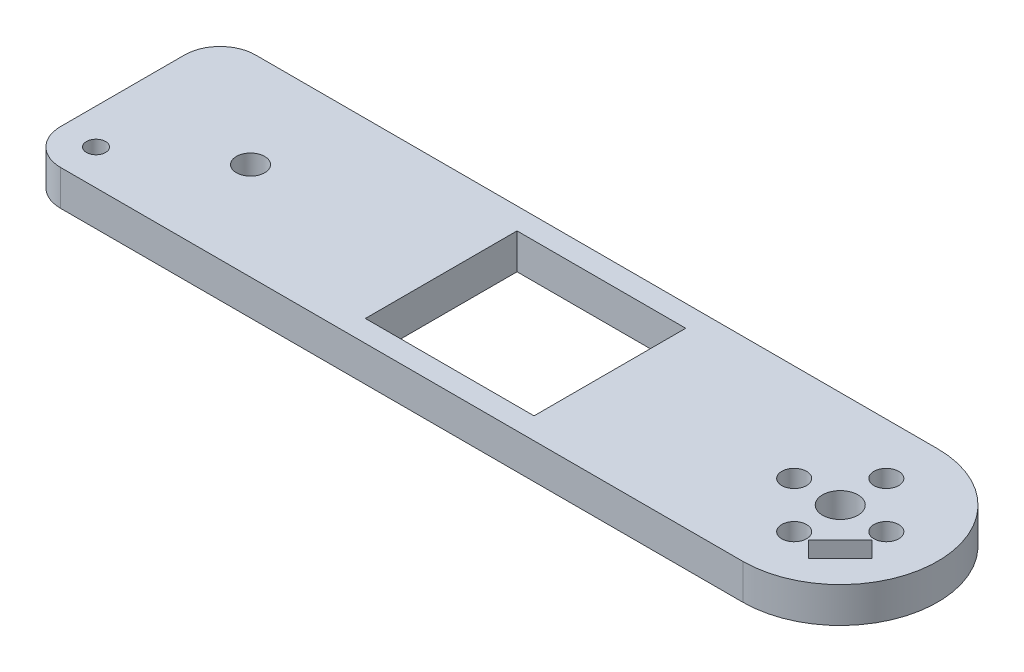
SolidWorks part; units mm, degrees
material "ABS"
ref_plane "Front Plane" through (0, 0, 0) normal (0, 0, 1) x (1, 0, 0)
ref_plane "Top Plane" through (0, 0, 0) normal (0, 1, 0) x (1, 0, 0)
ref_plane "Right Plane" through (0, 0, 0) normal (1, 0, 0) x (0, 0, -1)
sketch "Sketch1" plane through (0, 0, 0) normal (0, 1, 0) x (1, 0, 0)
  line L1 (87.5, -27.5) -> (-87.5, -27.5)
  line L2 (87.5, -27.5) -> (87.5, 27.5)
  line L3 (87.5, 27.5) -> (-87.5, 27.5)
  line L4 (-87.5, -27.5) -> (-87.5, 27.5)
  line L5 (87.5, -27.5) -> (-87.5, 27.5) construction
  line L6 (87.5, 27.5) -> (-87.5, -27.5) construction
  point P0 (0, 0)
  dimension "D1" = 175
  dimension "D2" = 55
extrude "Boss-Extrude1" add sketch "Sketch1" along normal blind 10
sketch "Sketch2" plane through (0, 0, 0) normal (0, -1, 0) x (1, 0, 0)
  line L0 (-87.5, 27.5) -> (-87.5, -27.5)
  line L1 (87.5, 27.5) -> (87.5, -27.5)
  line L2 (87.5, -27.5) -> (-87.5, -27.5) construction
  line L3 (0, 27.5) -> (0, 0) construction
  line L4 (-87.5, 27.5) -> (87.5, 27.5) construction
  line L5 (-87.5, 27.5) -> (-115, 27.5)
  line L6 (-115, 27.5) -> (-115, -27.5)
  line L7 (-115, -27.5) -> (-87.5, -27.5)
  line L8 (87.5, 27.5) -> (87.5, -27.5) construction
  line L9 (-87.5, -27.5) -> (-87.5, 27.5) construction
  arc A0 (-87.5, -27.5) -> (-87.5, 27.5) centre (-87.5, 0) cw construction
  arc A1 (87.5, -27.5) -> (87.5, 27.5) centre (87.5, 0) ccw
extrude "Boss-Extrude2" add sketch "Sketch2" against normal up to surface (10 mm away) up to face at (0, 10, 0)
sketch "Sketch4" plane through (0, 10, 0) normal (0, 1, 0) x (1, 0, 0)
  circle A0 centre (87.5, 0) radius 12.065
  dimension "D1" = 24.13
hole_wizard "M8 Clearance Hole1" positions "Sketch5" profile "Sketch6" hole size "M8" standard "ANSI Metric" end condition through all
sketch "Sketch5" plane through (0, 0, 0) normal (0, -1, 0) x (-1, 0, 0)
  point P0 (-87.5, 0)
sketch "Sketch6" plane through (87.5, 0, 0) normal (1, 0, 0) x (0, 0, -1)
  line L0 (0, 0) -> (0, 10)
  line L1 (0, 10) -> (5, 10)
  line L2 (5, 10) -> (5, 0)
  line L5 (5, 0) -> (0, 0)
  line L11 (0, -6.35) -> (0, 107.95) construction
  dimension "Thru Hole Dia." = 10
  dimension "Thru Hole Depth" = 10
hole_wizard "M6 Clearance Hole1" positions "Sketch9" profile "Sketch8" hole size "M6" standard "ANSI Metric" end condition through all
sketch "Sketch9" plane through (0, 10, 0) normal (0, 1, 0) x (1, 0, 0)
  circle A2 centre (87.5, 0) radius 13
  point P8 (87.5, 13)
  point P12 (74.5, 0)
  point P14 (100.5, 0)
  point P16 (87.5, -13)
  dimension "D2" = 26
sketch "Sketch8" plane through (87.5, 10, -13) normal (1, 0, 0) x (0, 0, 1)
  line L0 (0, 0) -> (0, 10)
  line L1 (0, 10) -> (3.5, 10)
  line L2 (3.5, 10) -> (3.5, 0)
  line L5 (3.5, 0) -> (0, 0)
  line L11 (0, -6.35) -> (0, 107.95) construction
  dimension "Thru Hole Dia." = 7
  dimension "Thru Hole Depth" = 10
fillet "Fillet1" radius 10 2 edges at (-115, 5, 27.5) (-115, 5, -27.5)
sketch "Sketch11" plane through (0, 0, 0) normal (0, -1, 0) x (1, 0, 0)
  line L1 (-24.9, -21.2) -> (17.5, -21.2)
  line L2 (-24.9, -21.2) -> (-24.9, 21.2)
  line L3 (-24.9, 21.2) -> (17.5, 21.2)
  line L4 (17.5, -21.2) -> (17.5, 21.2)
  line L5 (-24.9, -21.2) -> (17.5, 21.2) construction
  line L6 (-24.9, 21.2) -> (17.5, -21.2) construction
  point P4 (-3.7, 0)
  dimension "D1" = 42.4
  dimension "D2" = 70
extrude "Cut-Extrude3" cut sketch "Sketch11" against normal through all
sketch "Sketch12" plane through (0, 0, 0) normal (0, -1, 0) x (1, 0, 0)
  line L2 (-115, 17.5) -> (-115, -17.5) construction
  circle A0 centre (-78.9, 0) radius 4
  point P7 (-115, 0)
  dimension "D1" = 8
  dimension "D2" = 54
extrude "Cut-Extrude4" cut sketch "Sketch12" against normal through all
sketch "Sketch13" plane through (0, 0, 0) normal (0, -1, 0) x (1, 0, 0)
  line L0 (-24.9, -21.2) -> (17.5, -21.2) construction
  line L1 (17.5, 21.2) -> (22.5, 21.2)
  line L2 (17.5, 21.2) -> (17.5, -21.2)
  line L3 (17.5, -21.2) -> (22.5, -21.2)
  line L4 (22.5, 21.2) -> (22.5, -21.2)
  line L5 (17.5, 21.2) -> (22.5, -21.2) construction
  line L6 (17.5, -21.2) -> (22.5, 21.2) construction
  line L7 (-24.9, 21.2) -> (-24.9, -21.2) construction
  line L8 (-24.9, 21.2) -> (22.5, 21.2)
  line L9 (-24.9, 21.2) -> (-24.9, 21.4)
  line L10 (-24.9, 21.4) -> (22.5, 21.4)
  line L11 (22.5, 21.2) -> (22.5, 21.4)
  line L12 (-24.9, 21.2) -> (22.5, 21.4) construction
  line L13 (-24.9, 21.4) -> (22.5, 21.2) construction
  line L14 (22.5, -21.2) -> (-24.9, -21.2)
  line L15 (22.5, -21.2) -> (22.5, -21.4)
  line L16 (22.5, -21.4) -> (-24.9, -21.4)
  line L17 (-24.9, -21.2) -> (-24.9, -21.4)
  line L18 (22.5, -21.2) -> (-24.9, -21.4) construction
  line L19 (22.5, -21.4) -> (-24.9, -21.2) construction
  line L20 (-24.9, -21.4) -> (-25.1, -21.4)
  line L21 (-24.9, -21.4) -> (-24.9, 21.4)
  line L22 (-24.9, 21.4) -> (-25.1, 21.4)
  line L23 (-25.1, -21.4) -> (-25.1, 21.4)
  line L24 (-24.9, -21.4) -> (-25.1, 21.4) construction
  line L25 (-24.9, 21.4) -> (-25.1, -21.4) construction
  line L26 (17.5, 21.2) -> (-24.9, 21.2) construction
  point P4 (20, 0)
  point P12 (-1.2, 21.3)
  point P17 (-1.2, -21.3)
  point P21 (-25, 0)
  line M6 (17.5, -21.2) -> (-24.9, -21.2)
  line M7 (-24.9, -21.2) -> (-24.9, 21.2)
  line M8 (-24.9, 21.2) -> (17.5, 21.2)
  line M9 (17.5, 21.2) -> (17.5, -21.2)
  dimension "D1" = 5
  dimension "D2" = 0.2
  dimension "D3" = 0.2
  dimension "D4" = 0.2
  dimension "D5" = 42.4
  dimension "D6" = 23.7
extrude "Cut-Extrude5" cut sketch "Sketch13" against normal through all contours L23 L20 L17 L9 L22 M7 | L1 L11 L10 L9 M8 | L4 L1 L3 M9 | L17 L16 L15 L3 M6
sketch "Sketch14" plane through (0, 0, 0) normal (0, -1, 0) x (1, 0, 0)
  line L0 (91.5411, 13.0214) -> (100.5214, 4.0411)
  line L1 (91.5411, 13.0214) -> (96.0312, 17.5115)
  line L2 (100.5214, 4.0411) -> (105.0115, 8.5312)
  line L3 (96.0312, 17.5115) -> (105.0115, 8.5312)
  line L4 (83.9645, 3.5355) -> (91.0355, -3.5355) construction
  line L5 (87.5, 5) -> (87.5, -5) construction
  line L6 (87.5, 0) -> (96.0312, 8.5312) construction
  circle A1 centre (87.5, 0) radius 5 construction
  circle A2 centre (87.5, 0) radius 12.065 construction
  point P13 (87.5, 0)
  dimension "D4" = 45
  dimension "D1" = 45
  dimension "D2" = 12.7
  dimension "D3" = 6.35
extrude "Cut-Extrude6" cut sketch "Sketch14" against normal blind 12.7
sketch "Sketch15" plane through (52.2812, 0, 52.2812) normal (0.7071, 0, 0.7071) x (0.7071, 0, -0.7071)
  line L1 (55.5218, 0) -> (68.2218, 0) construction
  line L2 (55.5218, 0) -> (68.2218, 0) construction
  line L3 (55.5218, 10) -> (55.5218, 0) construction
  line L4 (55.5218, 10) -> (55.5218, 0) construction
  circle A0 centre (61.8718, 3) radius 3.375
  point P7 (61.8718, 0)
  dimension "D1" = 6.75
  dimension "D2" = 3
extrude "Cut-Extrude7" [suppressed] cut sketch "Sketch15" along normal through all and the other way up to surface
sketch "Sketch16" plane through (0, 0, 0) normal (0, -1, 0) x (1, 0, 0)
  circle A0 centre (-105, 17.5) radius 2.7
  arc A1 (-105, 27.5) -> (-115, 17.5) centre (-105, 17.5) ccw construction
  dimension "D1" = 5.4
extrude "Cut-Extrude8" cut sketch "Sketch16" against normal through all
